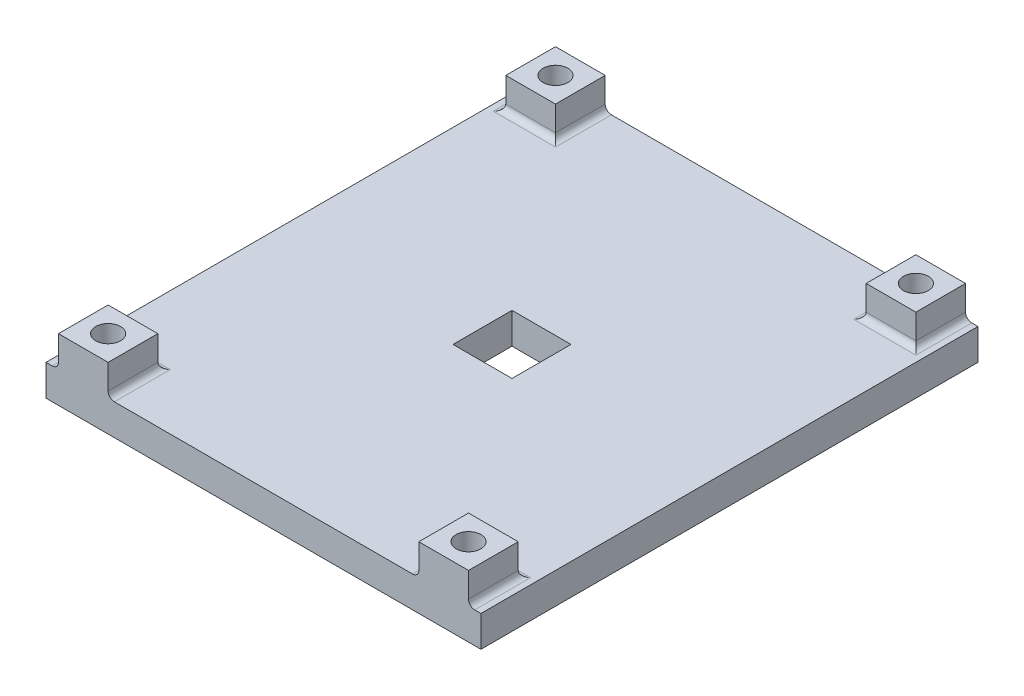
SolidWorks part; units mm, degrees
material "ABS"
ref_plane "前基準面" through (0, 0, 0) normal (0, 0, 1) x (1, 0, 0)
ref_plane "上基準面" through (0, 0, 0) normal (0, 1, 0) x (1, 0, 0)
ref_plane "右基準面" through (0, 0, 0) normal (1, 0, 0) x (0, 0, -1)
sketch "草圖1" plane through (0, 0, 0) normal (0, 1, 0) x (1, 0, 0)
  line L2 (-35, -40) -> (-35, 40)
  line L4 (35, -40) -> (35, 40)
  line L5 (-35, -40) -> (35, 40) construction
  line L6 (-35, 40) -> (35, -40) construction
  line L9 (-1000, 0) -> (49000, 0) construction
  line L10 (0, -1000) -> (0, 0) construction
  line L20 (-35, 40) -> (35, 40)
  line L21 (-35, -40) -> (35, -40)
  line L24 (0, 40) -> (0, 49000) construction
  point P0 (0, 0)
  dimension "D1" = 70
  dimension "D2" = 80
extrude "填料-伸長1" add sketch "草圖1" along normal blind 5
sketch "草圖3" plane through (0, 5, 0) normal (0, 1, 0) x (1, 0, 0)
  line L0 (-40, 0) -> (-84.1, 0) construction
  line L1 (-33, -40) -> (-25, -40)
  line L2 (-33, -40) -> (-33, -32)
  line L9 (0, 0) -> (0, 84.8027) construction
  line L28 (-35, -40) -> (35, -40) construction
  line L37 (-84.1, 0) -> (84.1, 0) construction
  line L38 (84.1, 0) -> (35, 0) construction
  line L41 (-33, -32) -> (-25, -32)
  line L42 (-25, -32) -> (-25, -40)
  line L68 (-33, 40) -> (-33, 32)
  line L69 (-33, 40) -> (-25, 40)
  line L70 (-25, 32) -> (-25, 40)
  line L71 (-33, 32) -> (-25, 32)
  line L72 (33, -40) -> (33, -32)
  line L73 (33, -40) -> (25, -40)
  line L74 (25, -32) -> (25, -40)
  line L75 (33, -32) -> (25, -32)
  line L76 (33, 40) -> (25, 40)
  line L77 (25, 32) -> (25, 40)
  line L78 (33, 32) -> (25, 32)
  line L79 (33, 40) -> (33, 32)
  line L80 (35, -40) -> (35, 40) construction
  dimension "D1" = 25
  dimension "D2" = 8
extrude "填料-伸長3" add sketch "草圖3" along normal blind 5
sketch "草圖12" plane through (0, 10, 0) normal (0, 1, 0) x (1, 0, 0)
  line L0 (0, 0) -> (-72.6137, 0) construction
  line L1 (0, 0) -> (0, 48.5097) construction
  line L3 (-4.75, -4.75) -> (4.75, -4.75)
  line L6 (-25, 40) -> (-33, 40) construction
  line L7 (-25, 32) -> (-25, 40) construction
  line L8 (-4.75, -4.75) -> (-4.75, 4.75)
  line L9 (-4.75, 4.75) -> (4.75, 4.75)
  line L10 (4.75, -4.75) -> (4.75, 4.75)
  line L11 (-4.75, -4.75) -> (4.75, 4.75) construction
  line L12 (-4.75, 4.75) -> (4.75, -4.75) construction
  circle A0 centre (-29, 36) radius 2
  circle A1 centre (-29, -36) radius 2
  circle A2 centre (29, -36) radius 2
  circle A3 centre (29, 36) radius 2
  point P15 (0, 0)
  dimension "D1" = 4
  dimension "D2" = 9.5
  dimension "D4" = 4
  dimension "D5" = 4
extrude "除料-伸長2" cut sketch "草圖12" against normal blind 10
fillet "圓角1" radius 1 12 edges at (29, 5, 32) (-29, 5, 32) (33, 5, 36) (33, 5, -36) (-33, 5, 36) (29, 5, -32) (25, 5, -36) (25, 5, 36) (-25, 5, 36) (-25, 5, -36) (-33, 5, -36) (-29, 5, -32)
